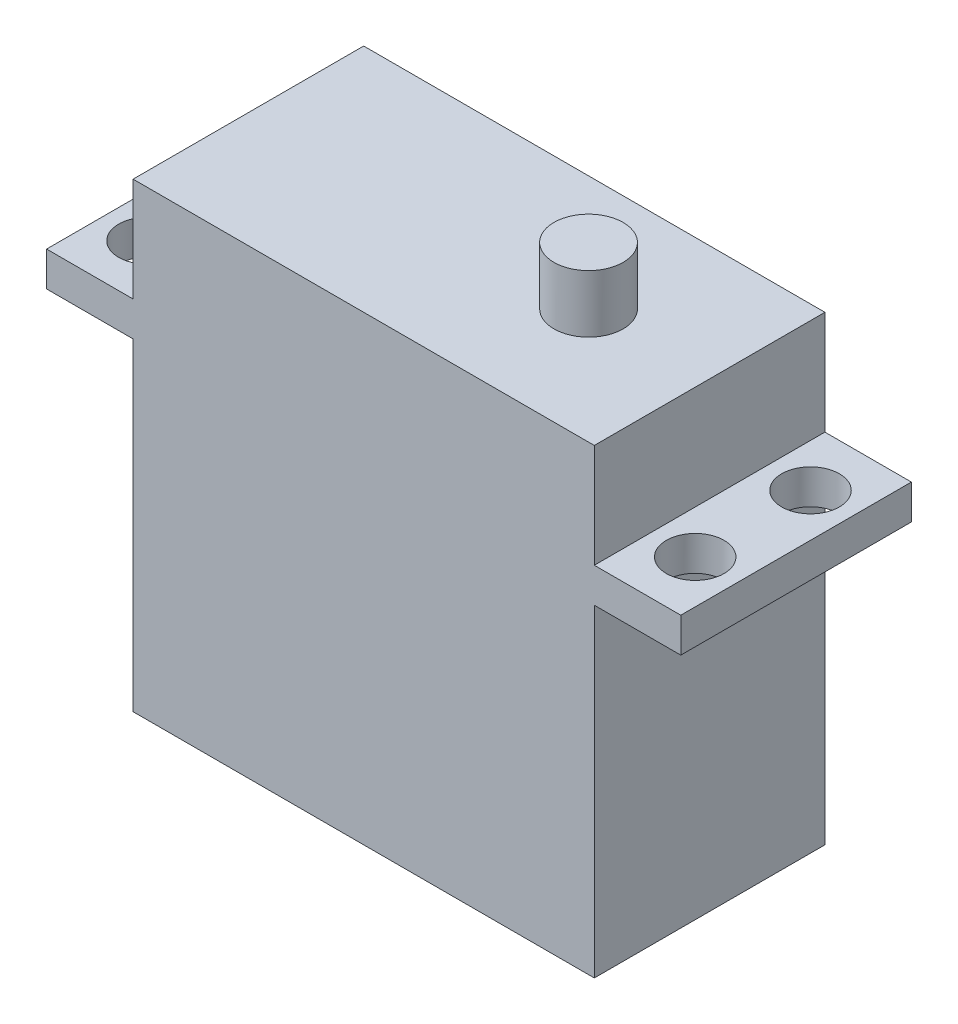
SolidWorks part; units mm, degrees
ref_plane "Front Plane" through (0, 0, 0) normal (0, 0, 1) x (1, 0, 0)
ref_plane "Top Plane" through (0, 0, 0) normal (0, 1, 0) x (1, 0, 0)
ref_plane "Right Plane" through (0, 0, 0) normal (1, 0, 0) x (0, 0, -1)
sketch "Sketch1" plane through (0, 0, 0) normal (0, 0, 1) x (1, 0, 0)
  line L1 (-20, -20) -> (20, -20)
  line L2 (-20, -20) -> (-20, 20)
  line L3 (-20, 20) -> (20, 20)
  line L4 (20, -20) -> (20, 20)
  line L5 (-20, -20) -> (20, 20) construction
  line L6 (-20, 20) -> (20, -20) construction
  point P0 (0, 0)
  dimension "D1" = 40
  dimension "D2" = 40
extrude "Boss-Extrude1" add sketch "Sketch1" along normal blind 20
sketch "Sketch2" plane through (0, 20, 0) normal (0, 1, 0) x (1, 0, 0)
  line L0 (20, -20) -> (20, 0) construction
  circle A0 centre (9.5, -10) radius 3
  point P4 (0, 0)
  point P5 (20, -10)
  dimension "D1" = 6
  dimension "D2" = 10.5
extrude "Boss-Extrude2" add sketch "Sketch2" along normal blind 5
sketch "Sketch3" plane through (-20, 0, 0) normal (-1, 0, 0) x (0, 0, 1)
  line L0 (0, 20) -> (0, -20) construction
  line L1 (0, 11) -> (20, 11)
  line L2 (0, 11) -> (0, 8)
  line L3 (0, 8) -> (20, 8)
  line L4 (20, 11) -> (20, 8)
  line L5 (20, 20) -> (20, -20) construction
  line L6 (20, -20) -> (0, -20) construction
  dimension "D1" = 28
  dimension "D2" = 3
extrude "Boss-Extrude3" add sketch "Sketch3" along normal blind 7.5
sketch "Sketch4" plane through (0, 11, 0) normal (0, 1, 0) x (1, 0, 0)
  line L1 (-27.5, 0) -> (-20, 0) construction
  line L2 (-27.5, -20) -> (-20, -20) construction
  circle A0 centre (-23.75, -5) radius 2.5
  circle A1 centre (-23.75, -15) radius 2.5
  point P5 (-23.75, 0)
  point P9 (-23.75, -20)
  point P10 (0, 0)
  point P12 (-31.5119, -14.4755)
  dimension "D1" = 5
  dimension "D3" = 5
  dimension "D2" = 5
  dimension "D4" = 5
extrude "Cut-Extrude1" cut sketch "Sketch4" against normal blind 7.5
mirror "Mirror1" about plane through (0, 0, 0) normal (1, 0, 0) of "Cut-Extrude1", "Boss-Extrude3"
